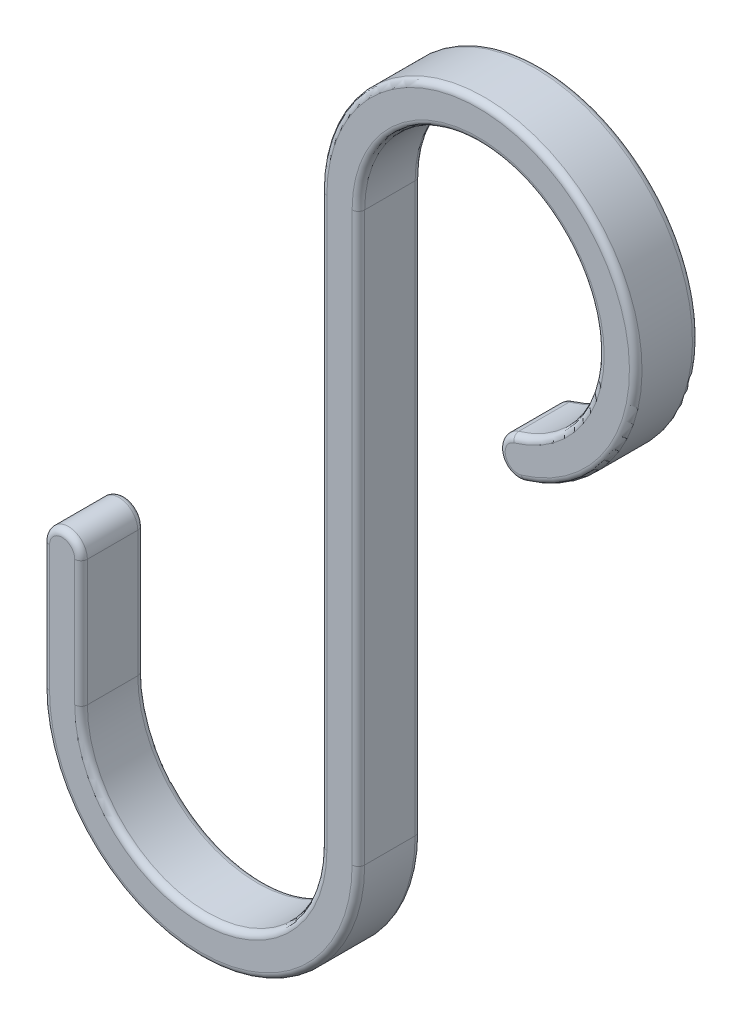
SolidWorks part; units mm, degrees
ref_plane "Front Plane" through (0, 0, 0) normal (0, 0, 1) x (1, 0, 0)
ref_plane "Top Plane" through (0, 0, 0) normal (0, 1, 0) x (1, 0, 0)
ref_plane "Right Plane" through (0, 0, 0) normal (1, 0, 0) x (0, 0, -1)
sketch "Sketch1" plane through (0, 0, 0) normal (0, 0, 1) x (1, 0, 0)
  line L0 (0, -22.5) -> (0, 22.5)
  line L1 (-23.5, -22.5) -> (-23.5, -12.5)
  line L2 (-33.7734, 0) -> (54.6599, 0) construction
  line L3 (1.5, -22.5) -> (1.5, 22.5)
  line L4 (-22, -22.5) -> (-22, -12.5)
  line L5 (-20.5, -22.5) -> (-20.5, -12.5)
  line L6 (-1.5, -22.5) -> (-1.5, 22.5)
  arc A0 (0, 22.5) -> (14.1422, 11.9583) centre (11, 22.5) cw
  arc A1 (1.5, -22.5) -> (-23.5, -22.5) centre (-11, -22.5) cw
  arc A2 (0, -22.5) -> (-22, -22.5) centre (-11, -22.5) cw
  arc A3 (1.5, 22.5) -> (13.7137, 13.3958) centre (11, 22.5) cw
  arc A4 (-1.5, -22.5) -> (-20.5, -22.5) centre (-11, -22.5) cw
  arc A5 (-1.5, 22.5) -> (14.5707, 10.5208) centre (11, 22.5) cw
  arc A6 (-23.5, -12.5) -> (-20.5, -12.5) centre (-22, -12.5) cw
  arc A7 (13.7137, 13.3958) -> (14.5707, 10.5208) centre (14.1422, 11.9583) ccw
  point P12 (0, 0)
  dimension "D1" = 11
  dimension "D3" = 12.5
  dimension "D2" = 22.5
  dimension "D7" = 1.5
  dimension "D8" = 1.5
extrude "Boss-Extrude1" add sketch "Sketch1" along normal blind 5 contours L1 A6 L5 A4 L6 A5 A7 A3 L3 A1
fillet "Fillet1" radius 0.5 10 edges at (-1.5, 0, 5) (18.4705, 32.5221, 5) (12.7047, 11.5299, 5) (16.6776, 30.1168, 5) (1.5, 0, 5) (-11, -35, 5) (-23.5, -17.5, 5) (-22, -11, 5) (-20.5, -17.5, 5) (-11, -32, 5)
fillet "Fillet2" radius 0.5 10 edges at (-11, -35, 0) (1.5, 0, 0) (16.6776, 30.1168, 0) (12.7047, 11.5299, 0) (18.4705, 32.5221, 0) (-1.5, 0, 0) (-11, -32, 0) (-20.5, -17.5, 0) (-22, -11, 0) (-23.5, -17.5, 0)
